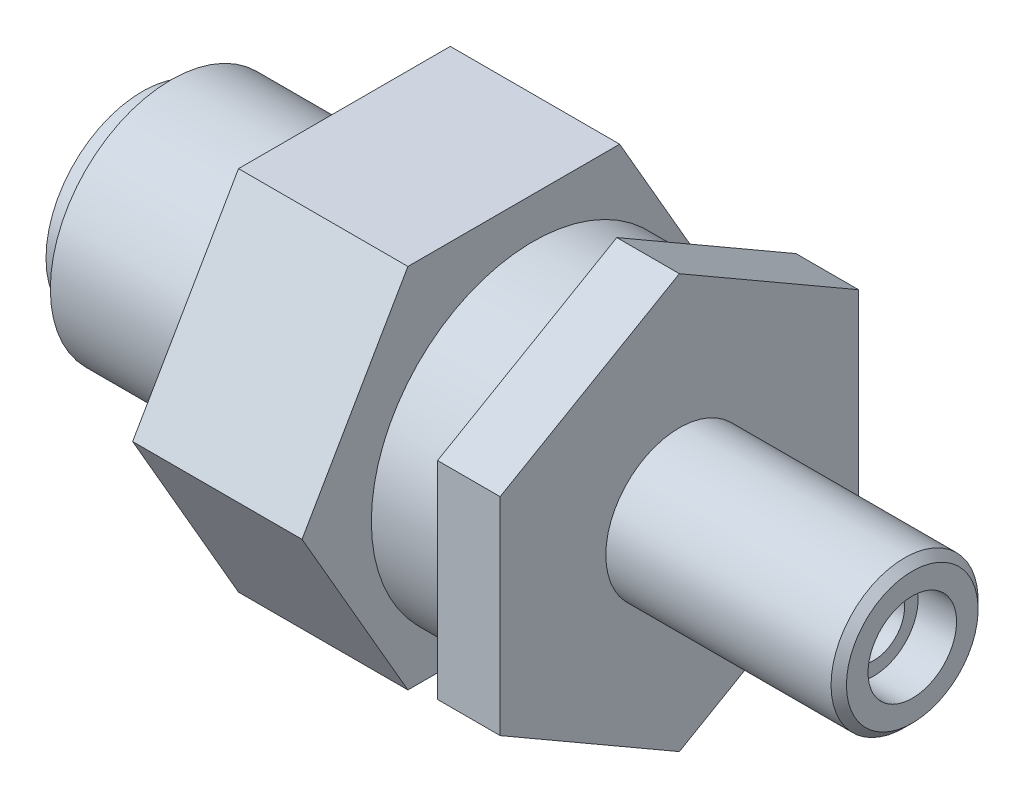
SolidWorks part; units mm, degrees
ref_plane "Front Plane" through (0, 0, 0) normal (0, 0, 1) x (1, 0, 0)
ref_plane "Top Plane" through (0, 0, 0) normal (0, 1, 0) x (1, 0, 0)
ref_plane "Right Plane" through (0, 0, 0) normal (1, 0, 0) x (0, 0, -1)
sketch "Sketch1" plane through (0, 0, 0) normal (0, 0, 1) x (1, 0, 0)
  line L0 (0, 0) -> (119.471, 0) construction
  line L1 (0, 0) -> (0, 5)
  line L2 (0, 5) -> (1.5, 5)
  line L3 (1.5, 5) -> (1.5, 6.275)
  line L4 (1.5, 6.275) -> (11, 6.275)
  line L5 (11, 6.275) -> (11, 8)
  line L6 (11, 8) -> (10.5, 8)
  line L7 (10.5, 8) -> (10.5, 11)
  line L8 (10.5, 11) -> (19.3, 11)
  line L9 (19.3, 11) -> (19.3, 6.5)
  line L10 (19.3, 6.5) -> (20.3, 6.5)
  line L11 (20.3, 6.5) -> (20.3, 8.4)
  line L12 (20.3, 8.4) -> (24.65, 8.4)
  line L13 (24.65, 8.4) -> (24.65, 10.75)
  line L14 (24.65, 10.75) -> (27.9, 10.75)
  line L15 (27.9, 10.75) -> (27.9, 3.82)
  line L16 (27.9, 3.82) -> (40, 3.82)
  line L17 (40, 3.82) -> (40, 2.3)
  line L18 (40, 2.3) -> (38, 2.3)
  line L19 (38, 2.3) -> (38, 1.6)
  line L20 (38, 1.6) -> (12, 1.6)
  line L21 (12, 1.6) -> (12, 0)
  line L22 (0, 0) -> (12, 0)
  dimension "D1" = 10
  dimension "D2" = 12.55
  dimension "D3" = 1.5
  dimension "D4" = 10.5
  dimension "D5" = 0.5
  dimension "D6" = 16
  dimension "D7" = 22
  dimension "D8" = 1
  dimension "D9" = 13
  dimension "D10" = 16.8
  dimension "D11" = 21.5
  dimension "D12" = 2
  dimension "D13" = 4.6
  dimension "D14" = 7.64
  dimension "D15" = 3.2
  dimension "D16" = 8.8
  dimension "D17" = 7.6
  dimension "D18" = 3.25
  dimension "D19" = 40
  dimension "D20" = 28
revolve "Revolve1" add sketch "Sketch1" angle 360 about L0
chamfer "Chamfer1" distance 0.4 angle 45 1 edges at (40, 0, 3.82)
sketch "Sketch2" plane through (27.9, 0, 0) normal (1, 0, 0) x (0, 0, -1)
  line L1 (0, 10.75) -> (-9.3098, 5.375)
  line L2 (-9.3098, 5.375) -> (-9.3098, -5.375)
  line L3 (-9.3098, -5.375) -> (0, -10.75)
  line L4 (0, -10.75) -> (9.3098, -5.375)
  line L5 (9.3098, -5.375) -> (9.3098, 5.375)
  line L6 (9.3098, 5.375) -> (0, 10.75)
  circle A0 centre (0, 0) radius 9.3098 construction
  circle A1 centre (0, 0) radius 10.75 construction
  circle A3 centre (0, 0) radius 11.9257
  dimension "D1" = 23.8515
extrude "Extrude1" cut sketch "Sketch2" against normal up to next
sketch "Sketch3" plane through (19.3, 0, 0) normal (1, 0, 0) x (0, 0, -1)
  line L1 (-5.5, 9.5263) -> (-11, 0)
  line L2 (-11, 0) -> (-5.5, -9.5263)
  line L3 (-5.5, -9.5263) -> (5.5, -9.5263)
  line L4 (5.5, -9.5263) -> (11, 0)
  line L5 (11, 0) -> (5.5, 9.5263)
  line L6 (5.5, 9.5263) -> (-5.5, 9.5263)
  circle A0 centre (0, 0) radius 9.5263 construction
  circle A1 centre (0, 0) radius 11 construction
  circle A2 centre (0, 0) radius 13.4912
  dimension "D1" = 26.9823
extrude "Extrude2" cut sketch "Sketch3" against normal up to next
